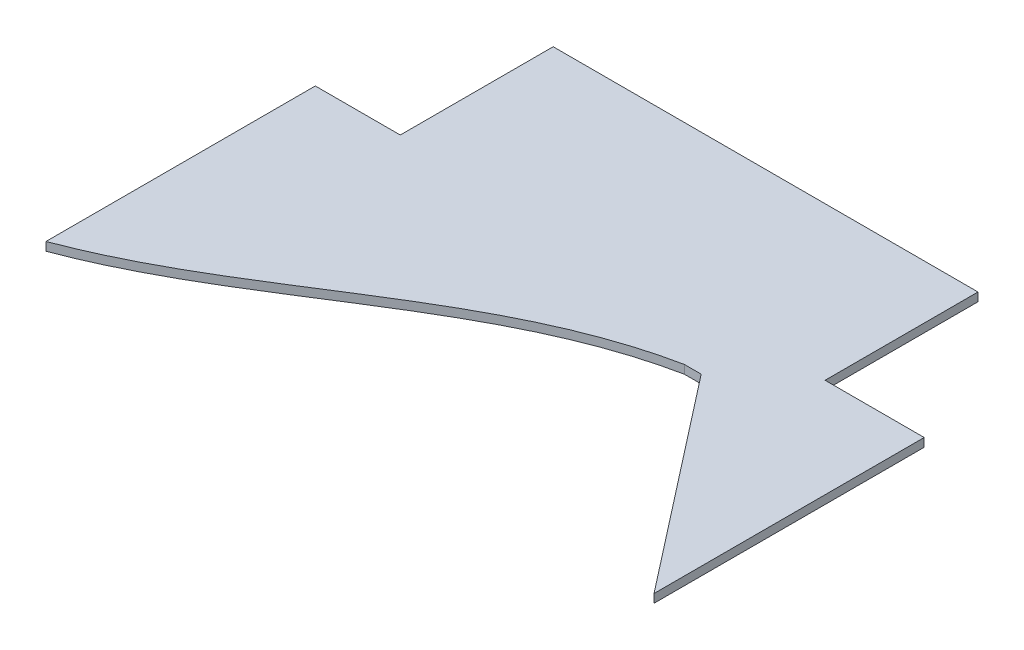
SolidWorks part; units mm, degrees
ref_plane "Front Plane" through (0, 0, 0) normal (0, 0, 1) x (1, 0, 0)
ref_plane "Top Plane" through (0, 0, 0) normal (0, 1, 0) x (1, 0, 0)
ref_plane "Right Plane" through (0, 0, 0) normal (1, 0, 0) x (0, 0, -1)
sketch "Sketch1" plane through (0, 0, 0) normal (0, 1, 0) x (1, 0, 0)
  line L0 (-75, -37) -> (-75, -97)
  line L1 (-75, -37) -> (75, -37)
  line L2 (-75, -37) -> (-75, 37)
  line L3 (-75, 37) -> (75, 37)
  line L4 (75, -37) -> (75, 37)
  line L5 (-75, -37) -> (75, 37) construction
  line L6 (-75, 37) -> (75, -37) construction
  line L7 (-105, -112.092) -> (-105, -97)
  line L8 (110, -112.3923) -> (51.2597, -37)
  line L9 (80.6299, -74.6961) -> (87.2068, -112.3923)
  line L10 (87.2068, -112.3923) -> (110, -112.3923)
  line L11 (-75, -17) -> (-105, -17)
  line L12 (-75, -17) -> (-75, -97)
  line L13 (-75, -97) -> (-105, -97)
  line L14 (-105, -17) -> (-105, -97)
  line L15 (75, -17) -> (110, -17)
  line L18 (110, -17) -> (110, -112.3923)
  circle A0 centre (40, -64.1393) radius 25 construction
  spline S0 degree 3 poles (45.2815, -37) (-12.2847, -48.6892) (-51.8248, -92.3041) (-105, -112.092) knots 0 0 0 0 1 1 1 1
  point P0 (0, 0)
  dimension "D8" = 50
  dimension "D1" = 150
  dimension "D2" = 74
  dimension "D3" = 35
  dimension "D4" = 60
  dimension "D5" = 80
  dimension "D6" = 30
  dimension "D9" = 35
extrude "Boss-Extrude1" add sketch "Sketch1" along normal blind 3
sketch "Sketch2" plane through (0, 3, 0) normal (0, 1, 0) x (1, 0, 0)
  line L0 (75, -17) -> (75, 37) construction
  circle A0 centre (40, -67.3967) radius 25 construction
  dimension "D1" = 50
  dimension "D2" = 35
